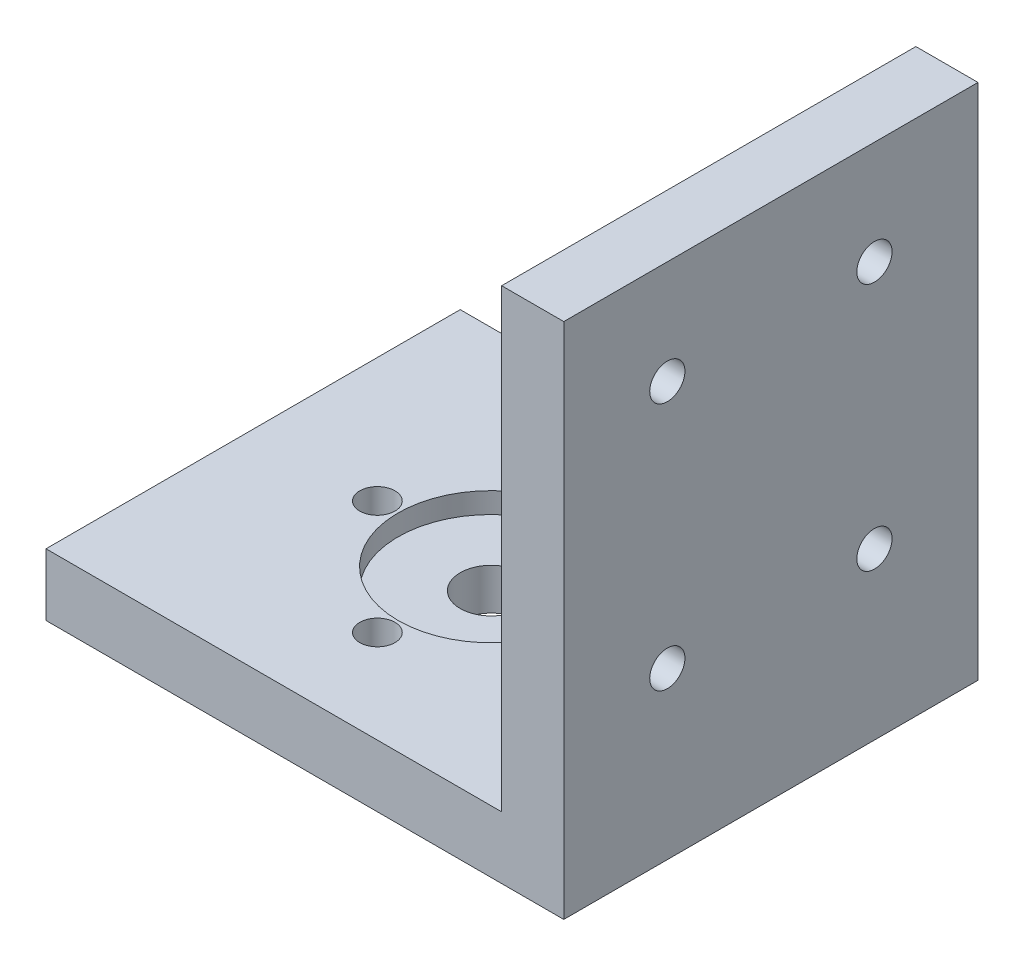
SolidWorks part; units mm, degrees
material "PLA"
ref_plane "Front Plane" through (0, 0, 0) normal (0, 0, 1) x (1, 0, 0)
ref_plane "Top Plane" through (0, 0, 0) normal (0, 1, 0) x (1, 0, 0)
ref_plane "Right Plane" through (0, 0, 0) normal (1, 0, 0) x (0, 0, -1)
sketch "Sketch1" plane through (0, 0, 0) normal (0, 1, 0) x (1, 0, 0)
  line L1 (0, 0) -> (50, 0)
  line L2 (0, 0) -> (0, 40)
  line L3 (0, 40) -> (50, 40)
  line L4 (50, 0) -> (50, 40)
  dimension "D1" = 50
  dimension "D2" = 40
extrude "Boss-Extrude1" add sketch "Sketch1" along normal blind 50
sketch "Sketch2" plane through (0, 0, 0) normal (0, 0, 1) x (1, 0, 0)
  line L1 (0, 50) -> (44, 50)
  line L2 (0, 50) -> (0, 6)
  line L3 (0, 6) -> (44, 6)
  line L4 (44, 50) -> (44, 6)
  dimension "D1" = 44
  dimension "D2" = 44
extrude "Cut-Extrude1" cut sketch "Sketch2" against normal blind 50 contours L2 L1 L4 L3
sketch "Sketch3" plane through (44, 0, 0) normal (-1, 0, 0) x (0, 0, 1)
  line L0 (-40, 50) -> (0, 50) construction
  line L1 (-40, 50) -> (-40, 6) construction
  line L2 (-20, 50) -> (-20, 6) construction
  line L3 (-40, 6) -> (0, 6) construction
  line L4 (-40, 28) -> (0, 28) construction
  line L5 (0, 50) -> (0, 6) construction
  circle A0 centre (-30, 40) radius 1.7
  circle A1 centre (-10, 40) radius 1.7
  circle A2 centre (-10, 16) radius 1.7
  circle A3 centre (-30, 16) radius 1.7
  dimension "D1" = 3.4
  dimension "D2" = 10
  dimension "D3" = 10
extrude "Cut-Extrude3" cut sketch "Sketch3" against normal through all contours A0 | A1 | A2 | A3
sketch "Sketch5" plane through (0, 6, 0) normal (0, 1, 0) x (1, 0, 0)
  line L0 (0, 40) -> (0, 0) construction
  circle A0 centre (23, 20) radius 9
  point P2 (0, 0)
  dimension "D1" = 18
  dimension "D2" = 23
extrude "Cut-Extrude4" cut sketch "Sketch5" against normal blind 2 contours A0
sketch "Sketch6" plane through (0, 4, 0) normal (0, 1, 0) x (1, 0, 0)
  circle A0 centre (23, 20) radius 3
  dimension "D1" = 6
extrude "Cut-Extrude5" cut sketch "Sketch6" against normal through all contours A0
sketch "Sketch7" plane through (0, 6, 0) normal (0, 1, 0) x (1, 0, 0)
  circle A0 centre (23, 20) radius 11
  circle A1 centre (12, 20) radius 1.7
  circle A2 centre (23, 31) radius 1.7
  circle A3 centre (34, 20) radius 1.7
  circle A4 centre (23, 9) radius 1.7
  dimension "D1" = 22
  dimension "D2" = 3.4
  dimension "D3" = 3.4
  dimension "D4" = 3.4
  dimension "D5" = 3.4
extrude "Cut-Extrude6" cut sketch "Sketch7" against normal through all contours A3 | A2 | A1 | A4
